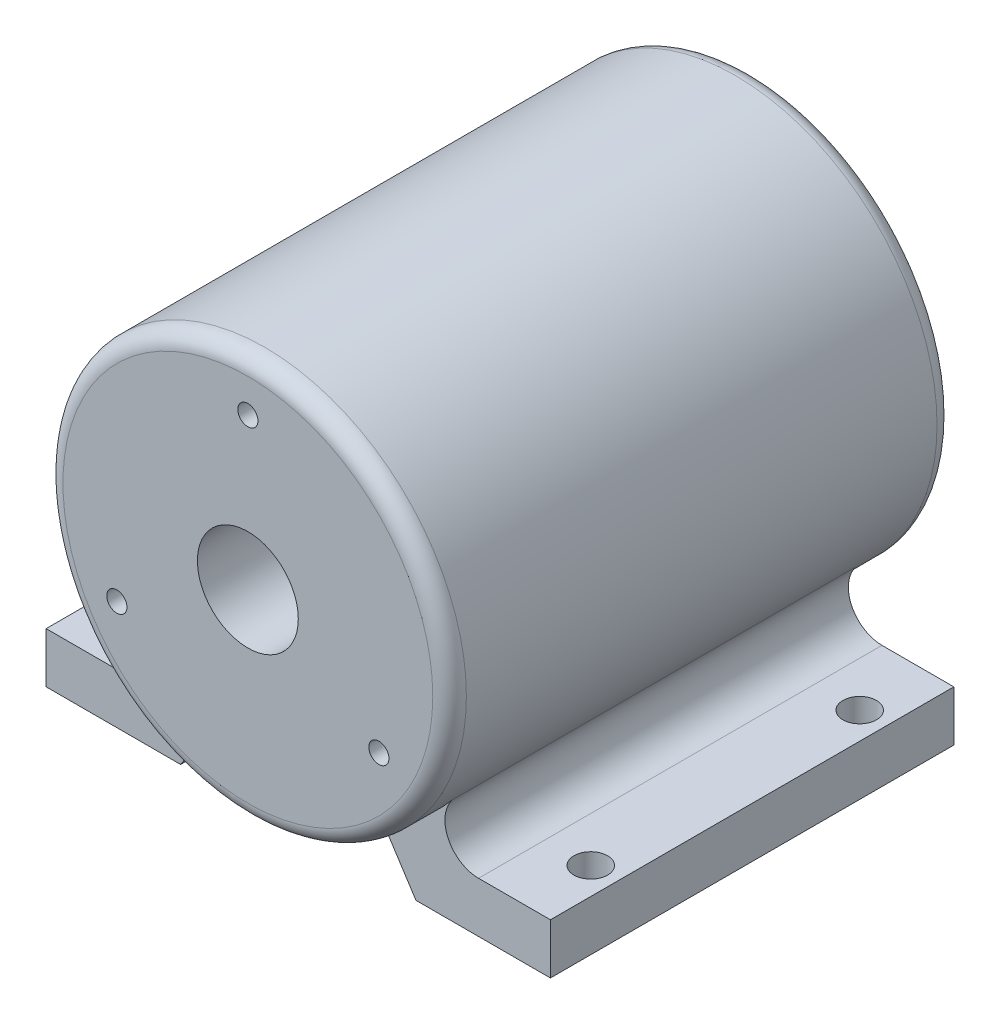
SolidWorks part; units mm, degrees
ref_plane "前基準面" through (0, 0, 0) normal (0, 0, 1) x (1, 0, 0)
ref_plane "上基準面" through (0, 0, 0) normal (0, 1, 0) x (1, 0, 0)
ref_plane "右基準面" through (0, 0, 0) normal (1, 0, 0) x (0, 0, -1)
sketch "草圖1" plane through (0, 0, 0) normal (0, 0, 1) x (1, 0, 0)
  circle A0 centre (0, 0) radius 6
  dimension "D1" = 12
extrude "填料-伸長1" add sketch "草圖1" along normal blind 15
sketch "草圖3" plane through (0, 0, 0) normal (0, 0, -1) x (-1, 0, 0)
  circle A0 centre (0, 0) radius 4
  circle A1 centre (0, 0) radius 6 construction
  dimension "D1" = 8
extrude "填料-伸長3" add sketch "草圖3" along normal blind 1
fillet "圓角2" radius 0.5 2 edges at (6, 0, 15) (6, 0, 0)
sketch "草圖4" plane through (0, 0, 0) normal (0, 0, 1) x (1, 0, 0)
  line L0 (0, 0) -> (0, -6.7483) construction
  line L1 (7.5, -7) -> (3.5, -7)
  line L2 (7.5, -7) -> (7.5, -5.5)
  line L3 (7.5, -5.5) -> (3.5, -5.5)
  line L4 (3.5, -7) -> (3.5, -5.5)
  line L5 (3.5, -7) -> (2.5, -5.4544)
  arc A0 (4.5959, -3.8571) -> (5.3619, -5.5) centre (5.3619, -4.5) ccw
  circle A1 centre (0, 0) radius 6 construction
  arc A2 (0, -6) -> (4.5959, -3.8571) centre (0, 0) ccw
  dimension "D1" = 13
  dimension "D5" = 1
  dimension "D2" = 15
  dimension "D3" = 4
  dimension "D4" = 1.5
  dimension "D6" = 2.5
extrude "填料-伸長4" add sketch "草圖4" along normal mid plane 12 from offset 7.5 contours L4 L1 L2 L3 | A2 L5 L4 L3 A0
hole_wizard "Ø1.0mm 定位孔1" positions "草圖5" profile "草圖6" hole size "Ø1.0" standard "ISO" end condition through all
sketch "草圖5" plane through (0, -5.5, 0) normal (0, 1, 0) x (1, 0, 0)
  line L0 (7.5, -7.5) -> (8.618, -7.5) construction
  line L1 (7.5, -13.5) -> (7.5, -1.5) construction
  point P0 (6.7, -3.5)
  point P11 (6.7, -11.5)
  dimension "D1" = 8
  dimension "D2" = 0.8
sketch "草圖6" plane through (6.7, -5.5, 3.5) normal (1, 0, 0) x (0, 0, 1)
  line L0 (0, 0) -> (0, 1.5)
  line L1 (0, 1.5) -> (0.5, 1.5)
  line L2 (0.5, 1.5) -> (0.5, 0)
  line L5 (0.5, 0) -> (0, 0)
  line L11 (0, -6.35) -> (0, 107.95) construction
  dimension "貫穿孔直徑" = 1
  dimension "貫穿孔深度" = 1.5
mirror "鏡射1" about plane through (0, 0, 0) normal (1, 0, 0) of "Ø1.0mm 定位孔1", "填料-伸長4"
fillet "圓角3" radius 0.2 2 edges at (-4, 0, 0) (-4, 0, -1)
sketch "草圖7" plane through (0, 0, 15) normal (0, 0, 1) x (1, 0, 0)
  circle A0 centre (0, 0) radius 1.5
  dimension "D1" = 3
extrude "除料-伸長1" cut sketch "草圖7" against normal through all
sketch "草圖8" plane through (0, 0, 15) normal (0, 0, 1) x (1, 0, 0)
  circle A0 centre (0, 0) radius 4.5 construction
  arc A1 (0.4635, 4.6875) -> (-0.4635, 4.6875) centre (0, 4.5) ccw construction
  arc A4 (-1.1257, 4.0982) -> (-4.112, -1.0742) centre (0, 0) ccw construction
  arc A5 (-0.4635, 4.6875) -> (-1.1257, 4.0982) centre (-1.3905, 5.0625) cw construction
  arc A6 (0.4635, 4.6875) -> (1.1257, 4.0982) centre (1.3905, 5.0625) ccw construction
  arc A7 (3.8277, -2.7452) -> (4.2913, -1.9423) centre (3.8971, -2.25) ccw construction
  arc A8 (4.2913, -1.9423) -> (4.112, -1.0742) centre (5.0795, -1.327) cw construction
  arc A9 (3.8277, -2.7452) -> (2.9863, -3.024) centre (3.689, -3.7355) ccw construction
  arc A10 (-4.2913, -1.9423) -> (-3.8277, -2.7452) centre (-3.8971, -2.25) ccw construction
  arc A11 (-3.8277, -2.7452) -> (-2.9863, -3.024) centre (-3.689, -3.7355) cw construction
  arc A12 (-4.2913, -1.9423) -> (-4.112, -1.0742) centre (-5.0795, -1.327) ccw construction
  arc A13 (-2.9863, -3.024) -> (2.9863, -3.024) centre (0, 0) ccw
  arc A14 (4.112, -1.0742) -> (1.1257, 4.0982) centre (0, 0) ccw construction
  point P27 (0, 0)
  dimension "D1" = 9
  dimension "D2" = 1
  dimension "D4" = 8.5
  dimension "D3" = 1
  dimension "D5" = 1
  dimension "D6" = 3
hole_wizard "M2 螺紋孔1" positions "草圖12" profile "草圖14" tap size "M2" standard "ISO"
sketch "草圖12" plane through (0, 0, 15) normal (0, 0, 1) x (1, 0, 0)
  point P0 (0, 4.5)
  point P3 (3.8971, -2.25)
  point P6 (-3.8971, -2.25)
sketch "草圖14" plane through (0, 4.5, 15) normal (1, 0, 0) x (0, -1, 0)
  line L0 (0, 0) -> (0, 2.6803)
  line L1 (0, 2.6803) -> (0.3, 2.5)
  line L2 (0.3, 2.5) -> (0.3, 0)
  line L5 (0.3, 0) -> (0, 0)
  line L10 (0, 2.6803) -> (-0.3, 2.5) construction
  line L11 (0, -6.35) -> (0, 107.95) construction
  dimension "螺孔鑽直徑" = 0.6
  dimension "螺孔鑽深度" = 2.5
  dimension "導頭角度" = 118
cosmetic thread "鑽孔螺紋1" parameters "D1"=2.5, "D2"=2
cosmetic thread "鑽孔螺紋2" parameters "D1"=2.5, "D2"=2
cosmetic thread "鑽孔螺紋3" parameters "D1"=2.5, "D2"=2
